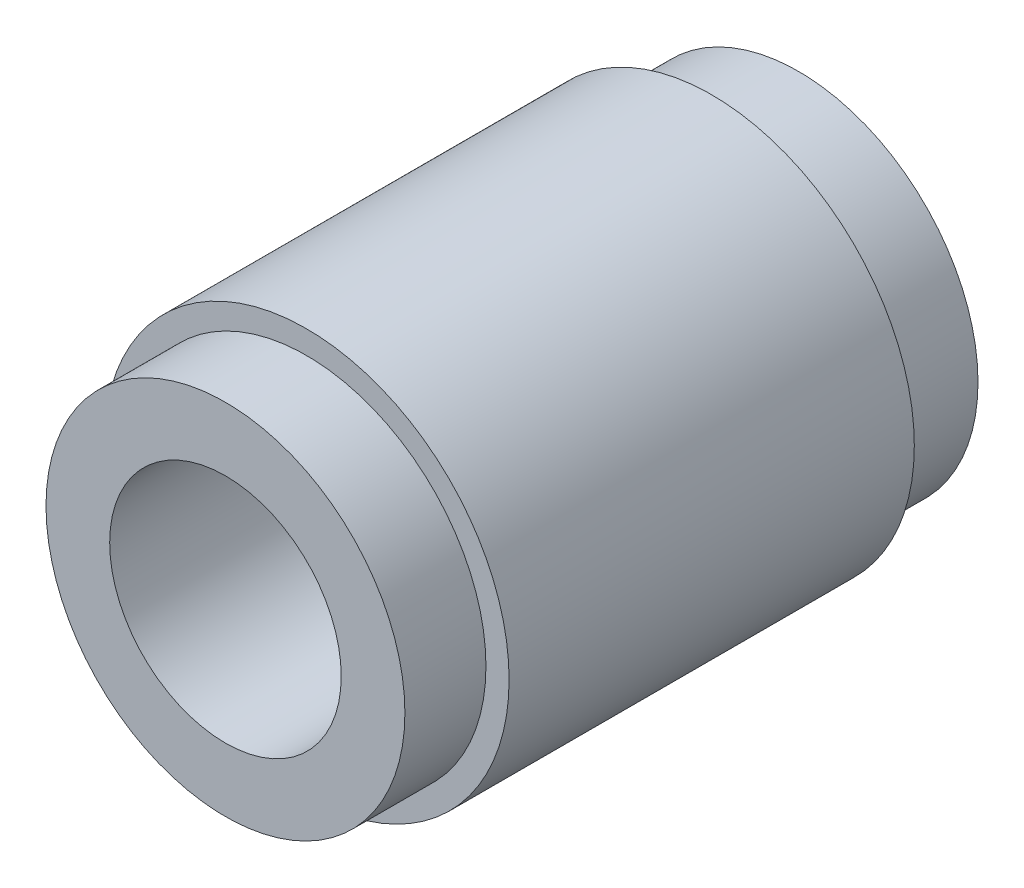
SolidWorks part; units mm, degrees
ref_plane "Front Plane" through (0, 0, 0) normal (0, 0, 1) x (1, 0, 0)
ref_plane "Top Plane" through (0, 0, 0) normal (0, 1, 0) x (1, 0, 0)
ref_plane "Right Plane" through (0, 0, 0) normal (1, 0, 0) x (0, 0, -1)
sketch "Sketch2" plane through (0, 0, 0) normal (0, 0, 1) x (1, 0, 0)
  circle A0 centre (0, 0) radius 3.1
  circle A1 centre (0, 0) radius 2
  dimension "D1" = 4
  dimension "D2" = 6.2
extrude "Boss-Extrude1" add sketch "Sketch2" along normal blind 1.5
sketch "Sketch3" plane through (0, 0, 1.5) normal (0, 0, 1) x (1, 0, 0)
  circle A0 centre (0, 0) radius 2 construction
  circle A1 centre (0, 0) radius 2
  circle A2 centre (0, 0) radius 3.5
  dimension "D1" = 7
extrude "Boss-Extrude2" add sketch "Sketch3" along normal blind 7
sketch "Sketch4" plane through (0, 0, 8.5) normal (0, 0, 1) x (1, 0, 0)
  circle A0 centre (0, 0) radius 2 construction
  circle A1 centre (0, 0) radius 2
  circle A2 centre (0, 0) radius 3.1
  dimension "D1" = 6.2
extrude "Boss-Extrude3" add sketch "Sketch4" along normal blind 1.4
